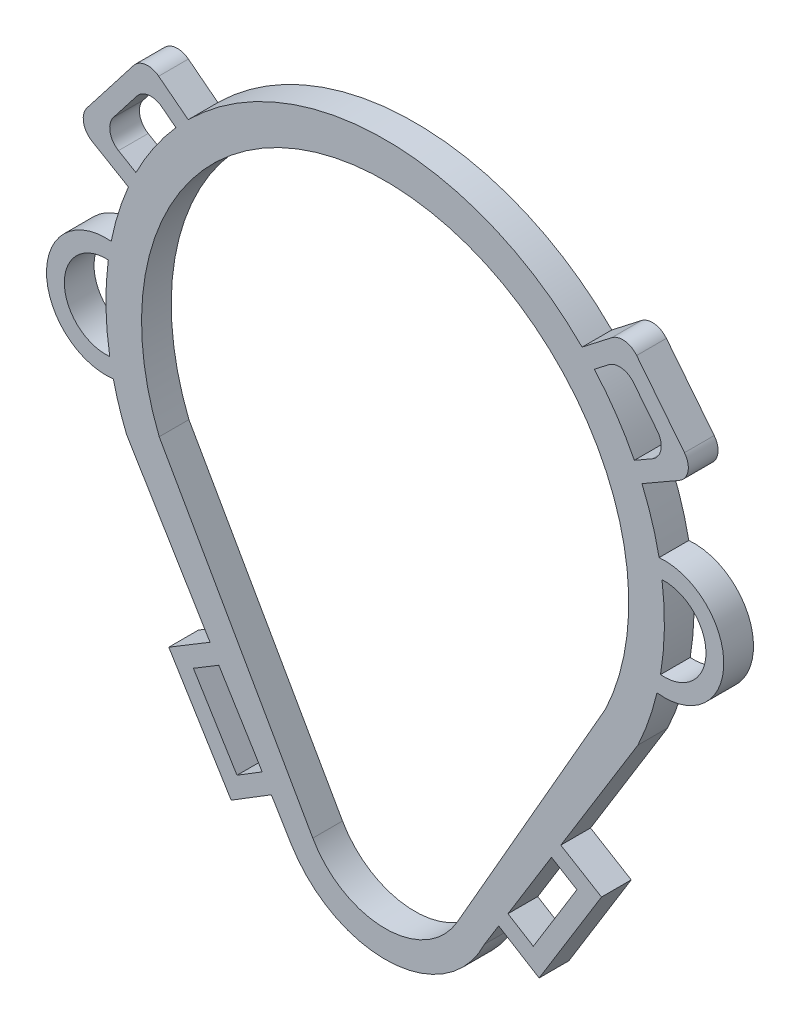
SolidWorks part; units mm, degrees
ref_plane "Front Plane" through (0, 0, 0) normal (0, 0, 1) x (1, 0, 0)
ref_plane "Top Plane" through (0, 0, 0) normal (0, 1, 0) x (1, 0, 0)
ref_plane "Right Plane" through (0, 0, 0) normal (1, 0, 0) x (0, 0, -1)
sketch "Sketch1" plane through (0, 0, 0) normal (0, 0, 1) x (1, 0, 0)
  line L0 (0, 41) -> (0, -67) construction
  line L5 (0, 0) -> (0, -54) construction
  line L6 (37.1057, -17.4403) -> (11.3127, -72.3172) construction
  line L7 (42.5358, -19.9925) -> (16.7428, -74.8694) construction
  line L8 (-38.0251, -15.3328) -> (-11.3182, -72.3056) construction
  line L9 (-43.5255, -17.735) -> (-16.7509, -74.8522) construction
  line L10 (-38.0251, -15.3328) -> (-12.1778, -60.9066)
  line L11 (-43.5255, -17.735) -> (-15.8341, -63.5669)
  line L12 (37.1057, -17.4403) -> (12.1446, -60.9649)
  line L13 (42.5358, -19.9925) -> (16.7077, -61.9433)
  arc A0 (37.1057, -17.4403) -> (-38.0251, -15.3328) centre (0, 0) ccw
  arc A2 (42.5358, -19.9925) -> (-43.5255, -17.735) centre (0, 0) ccw
  arc A4 (-12.1778, -60.9066) -> (12.1446, -60.9649) centre (0, -54) ccw
  arc A5 (-16.7509, -74.8522) -> (16.7428, -74.8694) centre (0, -67) ccw construction
  arc A6 (-11.3182, -72.3056) -> (11.3127, -72.3172) centre (0, -67) ccw construction
  arc A7 (-15.8341, -63.5669) -> (16.7077, -61.9433) centre (0, -54) ccw
  dimension "D1" = 6
  dimension "D2" = 41
  dimension "D3" = 14
  dimension "D6" = 18.4999
  dimension "D4" = 67
  dimension "D5" = 54
extrude "Boss-Extrude1" add sketch "Sketch1" along normal blind 5
sketch "Sketch2" plane through (0, 0, 5) normal (0, 0, 1) x (1, 0, 0)
  line L4 (0, 49.5385) -> (0, -93.5909) construction
  line L18 (27.9925, -43.6143) -> (20.6756, -55.4986)
  line L19 (16.7077, -61.9433) -> (42.5358, -19.9925) construction
  line L20 (20.6756, -55.4986) -> (24.9333, -58.12)
  line L21 (24.9333, -58.12) -> (32.2731, -46.1983)
  line L22 (32.2731, -46.1983) -> (27.9925, -43.6143)
  line L23 (25.9152, -62.2475) -> (36.4143, -45.194)
  line L24 (36.4143, -45.194) -> (26.997, -39.5091)
  line L25 (26.997, -39.5091) -> (16.5481, -56.4805)
  line L26 (16.5481, -56.4805) -> (25.9152, -62.2475)
  line L27 (-16.5481, -56.4805) -> (-25.9152, -62.2475)
  line L28 (-26.997, -39.5091) -> (-16.5481, -56.4805)
  line L29 (-36.4143, -45.194) -> (-26.997, -39.5091)
  line L30 (-25.9152, -62.2475) -> (-36.4143, -45.194)
  line L31 (-32.2731, -46.1983) -> (-27.9925, -43.6143)
  line L32 (-24.9333, -58.12) -> (-32.2731, -46.1983)
  line L33 (-20.6756, -55.4986) -> (-24.9333, -58.12)
  line L34 (-27.9925, -43.6143) -> (-20.6756, -55.4986)
  dimension "D1" = 3
  dimension "D2" = 5
  dimension "D4" = 14
  dimension "D5" = 5
extrude "Boss-Extrude2" add sketch "Sketch2" against normal blind 5
sketch "Sketch3" plane through (0, 0, 5) normal (0, 0, 1) x (1, 0, 0)
  line L0 (-35.214, 31.1284) -> (-37.5839, 32.9678)
  line L1 (-41.9377, 21.2186) -> (-44.876, 22.9491)
  line L2 (-41.7933, 32.4372) -> (-45.7234, 27.3735)
  line L3 (-35.214, 31.1284) -> (-41.9377, 21.2186)
  line L4 (-31.1514, 31.7728) -> (-38.1145, 37.1771)
  line L5 (-42.3238, 36.6466) -> (-50.1841, 26.519)
  line L6 (-41.0353, 17.2054) -> (-49.3367, 22.0947)
  line L7 (-31.1514, 31.7728) -> (-41.0353, 17.2054)
  line L8 (0, 0) -> (0, 76.5871) construction
  line L9 (31.1514, 31.7728) -> (41.0353, 17.2054)
  line L10 (41.0353, 17.2054) -> (49.5212, 22.0823)
  line L11 (42.3292, 36.6913) -> (50.3766, 26.5479)
  line L12 (31.1514, 31.7728) -> (38.1396, 37.1966)
  line L13 (35.214, 31.1284) -> (41.9377, 21.2186)
  line L14 (41.7986, 32.4819) -> (45.8142, 27.4204)
  line L15 (41.9377, 21.2186) -> (44.9589, 22.9548)
  line L16 (35.214, 31.1284) -> (37.6091, 32.9873)
  line L17 (-35.214, 31.1284) -> (-39.9539, 34.8072) construction
  line L18 (-39.9539, 34.8072) -> (-47.8142, 24.6797) construction
  line L19 (-31.1514, 31.7728) -> (-40.4844, 39.0165) construction
  line L20 (-40.4844, 39.0165) -> (-52.2749, 23.8252) construction
  line L21 (-41.0353, 17.2054) -> (-52.2749, 23.8252) construction
  line L22 (-41.9377, 21.2186) -> (-47.8142, 24.6797) construction
  circle A1 centre (-38.8928, 26.3885) radius 6 construction
  arc A2 (42.5358, -19.9925) -> (-43.5255, -17.735) centre (0, 0) ccw construction
  circle A3 centre (38.8928, 26.3885) radius 6 construction
  arc A4 (-37.5839, 32.9678) -> (-41.7933, 32.4372) centre (-39.4233, 30.5978) ccw
  arc A5 (-38.1145, 37.1771) -> (-42.3238, 36.6466) centre (-39.9539, 34.8072) ccw
  arc A6 (-49.3367, 22.0947) -> (-50.1841, 26.519) centre (-47.8142, 24.6797) cw
  arc A7 (-44.876, 22.9491) -> (-45.7234, 27.3735) centre (-43.3535, 25.5341) cw
  arc A8 (44.9589, 22.9548) -> (45.8142, 27.4204) centre (43.464, 25.5559) ccw
  arc A9 (49.5212, 22.0823) -> (50.3766, 26.5479) centre (48.0264, 24.6833) ccw
  arc A10 (42.3292, 36.6913) -> (38.1396, 37.1966) centre (39.979, 34.8267) ccw
  arc A11 (37.6091, 32.9873) -> (41.7986, 32.4819) centre (39.4484, 30.6173) cw
  point P29 (-39.9539, 34.8072)
  point P33 (-40.4844, 39.0165)
  point P46 (40.4844, 39.0165)
  point P49 (39.9539, 34.8072)
  dimension "D1" = 3
  dimension "D2" = 12
  dimension "D3" = 3
  dimension "D4" = 3
extrude "Boss-Extrude3" add sketch "Sketch3" against normal blind 5
sketch "Sketch4" plane through (0, 0, 5) normal (0, 0, 1) x (1, 0, 0)
  line L0 (45.8484, 6.0673) -> (45.8484, -7.7445)
  line L1 (42.8484, 8.2623) -> (42.8484, -9.9395)
  line L2 (0, 0) -> (0, 26.9586) construction
  line L3 (-42.8484, 8.2623) -> (-42.8484, -9.9395)
  line L4 (-45.8484, 6.0673) -> (-45.8484, -7.7445)
  arc A0 (42.5358, -19.9925) -> (43.2221, 18.4621) centre (0, 0) ccw construction
  arc A1 (45.8484, -7.7445) -> (45.8484, 6.0673) centre (46.9925, -0.8386) ccw
  arc A2 (42.8484, -9.9395) -> (42.8484, 8.2623) centre (46.9925, -0.8386) ccw
  arc A3 (-42.8484, -9.9395) -> (-42.8484, 8.2623) centre (-46.9925, -0.8386) cw
  arc A4 (-45.8484, -7.7445) -> (-45.8484, 6.0673) centre (-46.9925, -0.8386) cw
  dimension "D1" = 3
extrude "Boss-Extrude4" add sketch "Sketch4" against normal blind 5
